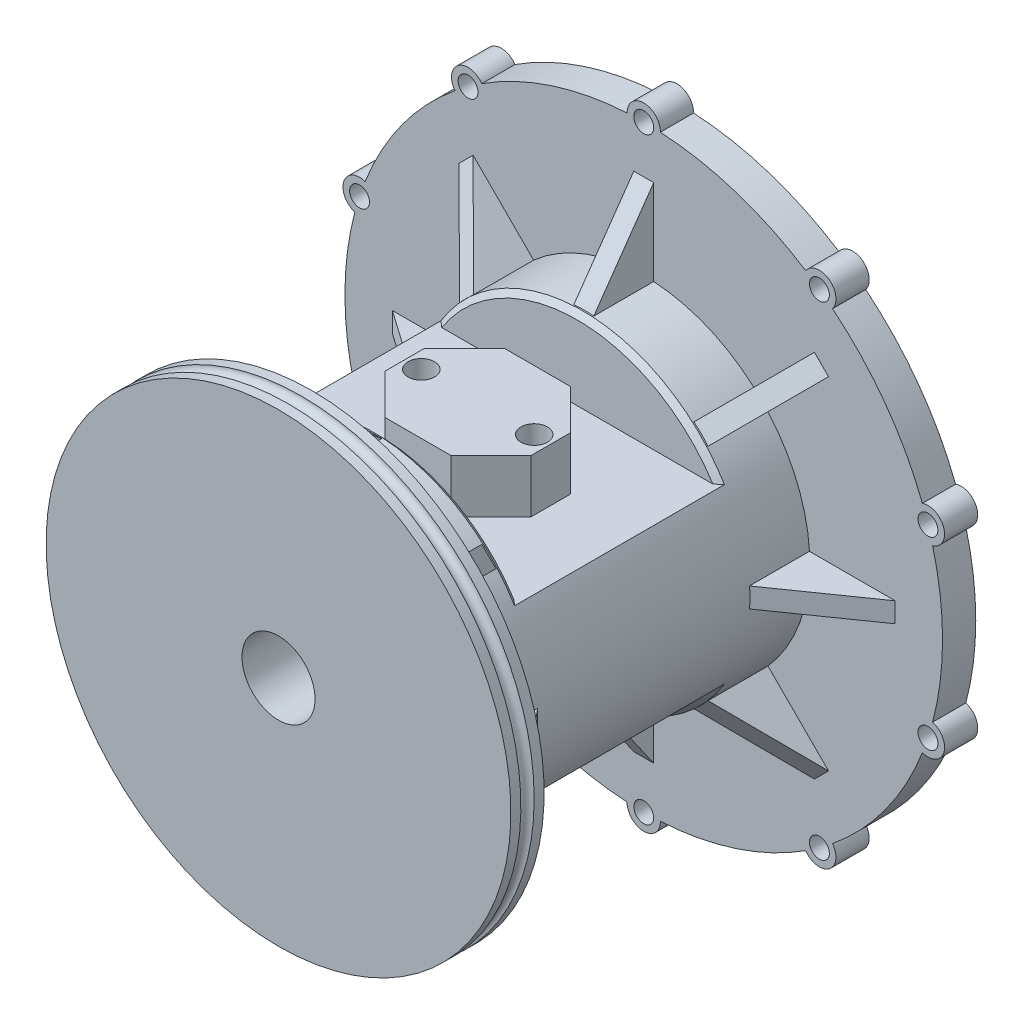
SolidWorks part; units mm, degrees
ref_plane "Front Plane" through (0, 0, 0) normal (0, 0, 1) x (1, 0, 0)
ref_plane "Top Plane" through (0, 0, 0) normal (0, 1, 0) x (1, 0, 0)
ref_plane "Right Plane" through (0, 0, 0) normal (1, 0, 0) x (0, 0, -1)
sketch "Sketch1" plane through (0, 0, 0) normal (0, 0, 1) x (1, 0, 0)
  circle A0 centre (0, 0) radius 45
  dimension "D1" = 90
extrude "Boss-Extrude1" add sketch "Sketch1" along normal blind 60
sketch "Sketch3" plane through (0, 0, 0) normal (1, 0, 0) x (0, 0, -1)
  line L0 (0, 27.5) -> (0, 0)
  line L1 (0, -45) -> (0, 45) construction
  line L2 (0, 0) -> (-60, 0)
  line L3 (-60, 45) -> (-60, -45) construction
  line L4 (-60, 0) -> (-60, 5.5)
  line L5 (-60, 5.5) -> (-2, 5.5)
  line L6 (-2, 5.5) -> (-2, 27.5)
  line L7 (0, 27.5) -> (-2, 27.5)
  line L8 (-5, 45) -> (-5, 25)
  line L9 (0, 45) -> (-60, 45) construction
  line L10 (-5, 25) -> (-55, 25)
  line L11 (-55, 25) -> (-55, 35)
  line L12 (-55, 35) -> (-60, 35)
  line L13 (-60, 35) -> (-60, 45)
  line L14 (-60, 45) -> (-5, 45)
  dimension "D1" = 5
  dimension "D2" = 35
  dimension "D3" = 25
  dimension "D4" = 27.5
  dimension "D5" = 5.5
  dimension "D6" = 2
  dimension "D7" = 5
revolve "Cut-Revolve1" cut sketch "Sketch3" angle 360 about L2
sketch "Sketch4" plane through (0, 0, 0) normal (1, 0, 0) x (0, 0, -1)
  line L0 (-14, 25) -> (11.6273, 25) construction
  line L1 (-5, 25) -> (-55, 25) construction
  line L2 (-5, 37.8533) -> (-14, 25)
  line L3 (-5, 45) -> (-5, -45) construction
  line L4 (-60, 35) -> (-60, -35) construction
  dimension "D1" = 55
  dimension "D2" = 46
rib "Rib8" sketch "Sketch4" sketch "Sketch4" thickness 3 extrusion direction parallel to sketch draft on no parameters "D1"=3
sketch "Sketch5" plane through (0, 0, 0) normal (1, 0, 0) x (0, 0, -1)
  line L0 (-55, 32.5519) -> (-46, 25)
  line L1 (-55, -35) -> (-55, 35) construction
  line L2 (-14, 25) -> (-55, 25) construction
  line L3 (-46, 25) -> (-67.9796, 25) construction
  line L4 (-60, 35) -> (-60, -35) construction
  dimension "D1" = 40
  dimension "D2" = 14
rib "Rib9" sketch "Sketch5" sketch "Sketch5" thickness 3 extrusion direction parallel to sketch draft on no parameters "D1"=3
pattern_circular "CirPattern1" count 8 over 360 about axis through (0, 0, 0) along (0, 0, 1) of "Rib9", "Rib8"
sketch "Sketch6" plane through (0, 0, 0) normal (1, 0, 0) x (0, 0, -1)
  line L0 (-14, 25) -> (-46, 25) construction
  line L1 (-15, 25) -> (-21, 25)
  line L2 (-15, 25) -> (-15, 13)
  line L3 (-15, 13) -> (-21, 13)
  line L4 (-21, 25) -> (-21, 13)
  line L5 (0, -27.5) -> (0, 27.5) construction
  line L6 (-39, 25) -> (-45, 25)
  line L7 (-39, 25) -> (-39, 13)
  line L8 (-39, 13) -> (-45, 13)
  line L9 (-45, 25) -> (-45, 13)
  line L10 (-60, 35) -> (-60, -35) construction
  line L11 (0, 0) -> (-21.7454, 0) construction
  line L12 (0, -45) -> (0, 45) construction
  line L13 (-45, -25) -> (-45, -13)
  line L14 (-39, -13) -> (-45, -13)
  line L15 (-39, -25) -> (-39, -13)
  line L16 (-39, -25) -> (-45, -25)
  line L17 (-21, -25) -> (-21, -13)
  line L18 (-15, -13) -> (-21, -13)
  line L19 (-15, -25) -> (-15, -13)
  line L20 (-15, -25) -> (-21, -25)
  dimension "D1" = 6
  dimension "D2" = 15
  dimension "D3" = 12
  dimension "D4" = 15
extrude "Cut-Extrude1" cut sketch "Sketch6" against normal mid plane 60
sketch "Sketch8" plane through (0, 0, 21) normal (0, 0, -1) x (-1, 0, 0)
  line L0 (-11, 13) -> (-11, 21)
  line L1 (21.3542, 13) -> (-21.3542, 13) construction
  line L2 (-11, 21) -> (11, 21)
  line L3 (11, 21) -> (11, 13)
  line L4 (11, 13) -> (26.2295, 13)
  line L5 (26.2295, 13) -> (26.2295, 31.5778)
  line L6 (26.2295, 31.5778) -> (-25.5913, 31.5778)
  line L7 (-25.5913, 31.5778) -> (-25.5913, 13)
  line L8 (-25.5913, 13) -> (-11, 13)
  line L9 (0, 0) -> (-23.45, 0) construction
  line L10 (-25.5913, -13) -> (-11, -13)
  line L11 (-25.5913, -31.5778) -> (-25.5913, -13)
  line L12 (26.2295, -31.5778) -> (-25.5913, -31.5778)
  line L13 (26.2295, -13) -> (26.2295, -31.5778)
  line L14 (11, -13) -> (26.2295, -13)
  line L15 (11, -21) -> (11, -13)
  line L16 (-11, -21) -> (11, -21)
  line L17 (-11, -13) -> (-11, -21)
  dimension "D1" = 22
  dimension "D2" = 11
  dimension "D3" = 8
extrude "Cut-Extrude2" cut sketch "Sketch8" against normal up to surface (18 mm away) up to face at (0, 19, 39)
chamfer "Chamfer1" distance 0.8 angle 45 4 edges at (0, 25, 45) (0, -25, 45) (0, -25, 15) (0, 25, 15)
chamfer "Chamfer2" distance 6 angle 45 8 edges at (-11, -17, 21) (11, -17, 21) (11, -17, 39) (-11, -17, 39) (11, 17, 39) (11, 17, 21) (-11, 17, 21) (-11, 17, 39)
sketch "Sketch10" plane through (0, -21, 0) normal (0, -1, 0) x (1, 0, 0)
  line L0 (11, 33) -> (11, 27) construction
  line L1 (-11, 33) -> (-11, 27) construction
  circle A0 centre (-8.5, 30) radius 2
  circle A1 centre (8.5, 30) radius 2
  dimension "D2" = 4
  dimension "D1" = 2.5
  dimension "D3" = 2.5
extrude "Cut-Extrude3" cut sketch "Sketch10" against normal through all
sketch "Sketch11" plane through (0, 0, 0) normal (0, 0, -1) x (-1, 0, 0)
  circle A0 centre (0, 45) radius 2.5
  circle A1 centre (0, 0) radius 45 construction
  circle A2 centre (26.4503, 36.4058) radius 2.5
  circle A3 centre (42.7975, 13.9058) radius 2.5
  circle A4 centre (42.7975, -13.9058) radius 2.5
  circle A5 centre (26.4503, -36.4058) radius 2.5
  circle A6 centre (0, -45) radius 2.5
  circle A7 centre (-26.4503, -36.4058) radius 2.5
  circle A8 centre (-42.7975, -13.9058) radius 2.5
  circle A9 centre (-42.7975, 13.9058) radius 2.5
  circle A10 centre (-26.4503, 36.4058) radius 2.5
  point P25 (0, 0)
  dimension "D1" = 5
  dimension "D2" = 10
extrude "Boss-Extrude2" add sketch "Sketch11" against normal blind 5
sketch "Sketch12" plane through (0, 0, 0) normal (0, 0, -1) x (-1, 0, 0)
  circle A0 centre (0, 45) radius 1.5
  circle A1 centre (26.4503, 36.4058) radius 1.5
  circle A2 centre (42.7975, 13.9058) radius 1.5
  circle A3 centre (42.7975, -13.9058) radius 1.5
  circle A4 centre (26.4503, -36.4058) radius 1.5
  circle A5 centre (0, -45) radius 1.5
  circle A6 centre (-26.4503, -36.4058) radius 1.5
  circle A7 centre (-42.7975, -13.9058) radius 1.5
  circle A8 centre (-42.7975, 13.9058) radius 1.5
  circle A9 centre (-26.4503, 36.4058) radius 1.5
  point P23 (0, 0)
  dimension "D1" = 3
  dimension "D2" = 10
extrude "Cut-Extrude4" cut sketch "Sketch12" against normal blind 5
sketch "Sketch13" plane through (0, 0, 0) normal (0, 1, 0) x (1, 0, 0)
  line L0 (35, -60) -> (35, -55) construction
  line L1 (0, 0) -> (0, -73.2021) construction
  circle A0 centre (35, -57.5) radius 1
  dimension "D1" = 2
revolve "Cut-Revolve2" cut sketch "Sketch13" angle 360 about L1
